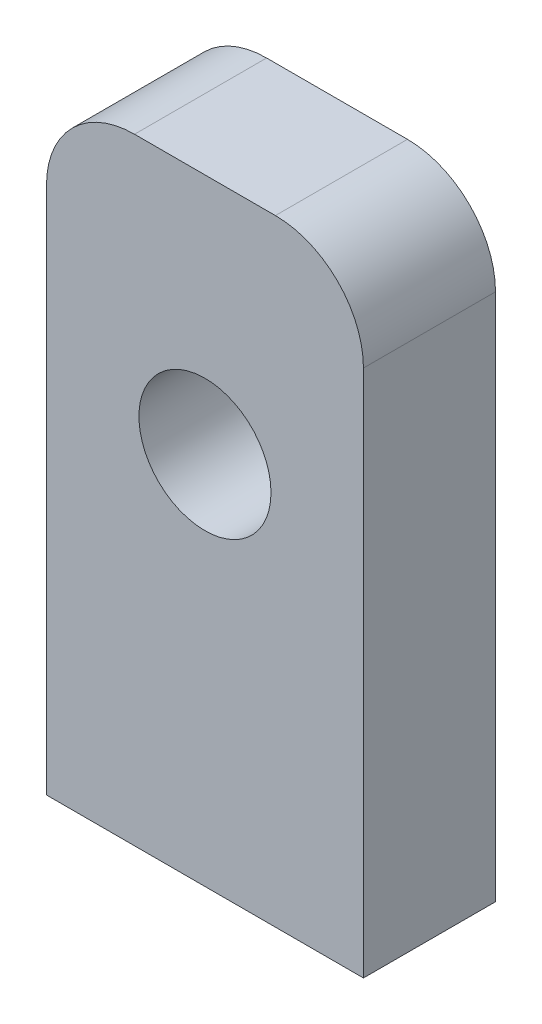
SolidWorks part; units mm, degrees
ref_plane "Plano frontal" through (0, 0, 0) normal (0, 0, 1) x (1, 0, 0)
ref_plane "Plano superior" through (0, 0, 0) normal (0, 1, 0) x (1, 0, 0)
ref_plane "Plano direito" through (0, 0, 0) normal (1, 0, 0) x (0, 0, -1)
sketch "Esboço1" plane through (0, 0, 0) normal (0, 0, 1) x (1, 0, 0)
  line L1 (0, 0) -> (7.2, 0)
  line L2 (0, 0) -> (0, 14)
  line L3 (0, 14) -> (7.2, 14)
  line L4 (7.2, 0) -> (7.2, 14)
  circle A0 centre (3.6, 8.5) radius 1.5
  dimension "D3" = 5.5
  dimension "D5" = 3
  dimension "D1" = 14
  dimension "D2" = 7.2
  dimension "D4" = 3.6
extrude "Ressalto-extrusão1" add sketch "Esboço1" along normal blind 3
fillet "Filete1" radius 2 2 edges at (0, 14, 1.5) (7.2, 14, 1.5)
